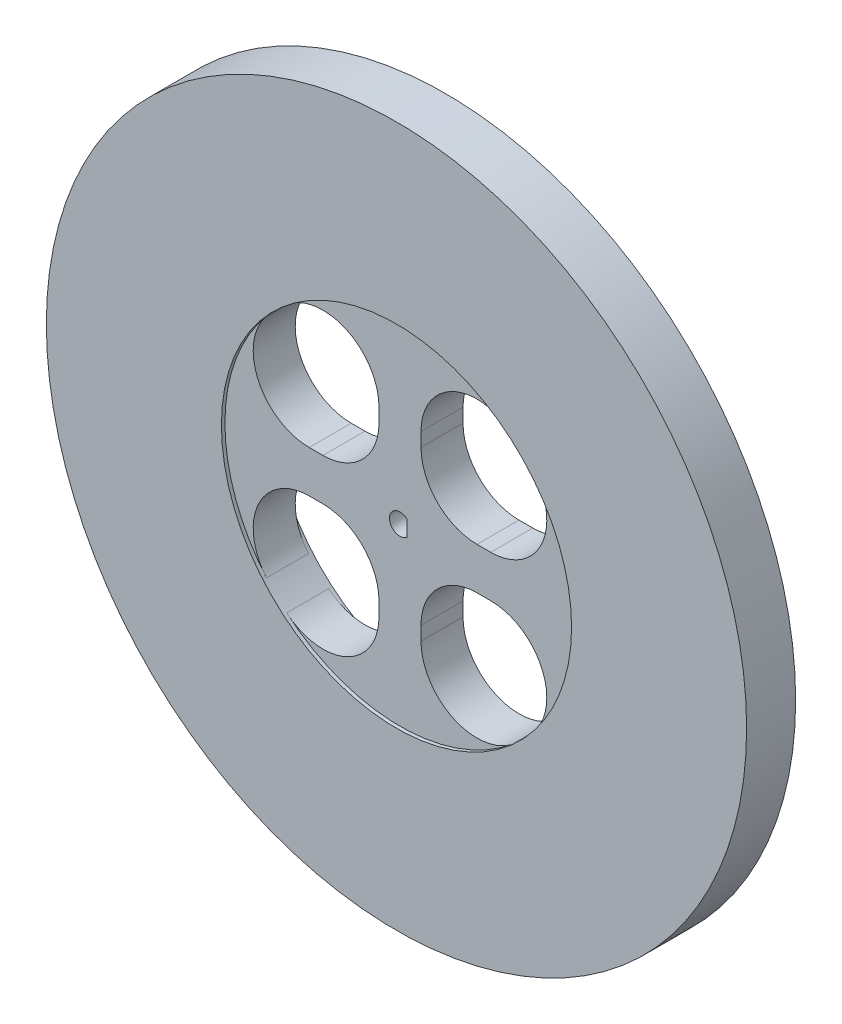
SolidWorks part; units mm, degrees
material "PET"
ref_plane "Front Plane" through (0, 0, 0) normal (0, 0, 1) x (1, 0, 0)
ref_plane "Top Plane" through (0, 0, 0) normal (0, 1, 0) x (1, 0, 0)
ref_plane "Right Plane" through (0, 0, 0) normal (1, 0, 0) x (0, 0, -1)
sketch "Sketch4" plane through (0, 0, 0) normal (0, 1, 0) x (1, 0, 0)
  line L0 (0, 11.6743) -> (0, -11.4125) construction
  line L2 (25, -3.5) -> (50, -3.5)
  line L3 (25, -3.5) -> (25, 3.5)
  line L4 (25, 3.5) -> (50, 3.5)
  line L5 (50, -3.5) -> (50, 3.5)
  line L6 (25, -3.5) -> (50, 3.5) construction
  line L7 (25, 3.5) -> (50, -3.5) construction
  point P3 (37.5, 0)
  dimension "D1" = 25
  dimension "D2" = 7
  dimension "D3" = 37.5
revolve "Revolve2" add sketch "Sketch4" angle 360 about L0
sketch "Sketch5" plane through (0, 0, 0) normal (0, 0, 1) x (1, 0, 0)
  line L0 (0, 25) -> (0, -25) construction
  line L1 (-3, 24.8193) -> (-3, 3)
  line L2 (-25, 0) -> (25, 0) construction
  line L3 (-24.8193, -3) -> (-3, -3)
  line L4 (3, 24.8193) -> (3, 3)
  line L5 (-24.8193, 3) -> (-3, 3)
  line L6 (3, 25) -> (3, -25) construction
  line L7 (-3, 25) -> (-3, -25) construction
  line L8 (-25, 3) -> (25, 3) construction
  line L9 (-25, -3) -> (25, -3) construction
  line L10 (3, 3) -> (24.8193, 3)
  line L11 (-3, -3) -> (-3, -24.8193)
  line L12 (3, -3) -> (24.8193, -3)
  line L13 (3, -3) -> (3, -24.8193)
  arc A0 (-24.8193, 3) -> (-24.8193, -3) centre (0, 0) ccw
  circle A1 centre (0, 0) radius 25 construction
  arc A2 (-3, 24.8193) -> (-24.8193, 3) centre (0, 0) ccw construction
  arc A3 (-24.8193, -3) -> (-3, -24.8193) centre (0, 0) ccw construction
  arc A4 (-3, -24.8193) -> (3, -24.8193) centre (0, 0) ccw
  arc A5 (3, -24.8193) -> (24.8193, -3) centre (0, 0) ccw construction
  arc A6 (24.8193, -3) -> (24.8193, 3) centre (0, 0) ccw
  arc A7 (24.8193, 3) -> (3, 24.8193) centre (0, 0) ccw construction
  arc A8 (3, 24.8193) -> (-3, 24.8193) centre (0, 0) ccw
  dimension "D1" = 3
  dimension "D2" = 3
extrude "Boss-Extrude3" add sketch "Sketch5" along normal blind 3 and the other way blind 3
fillet "Fillet2" radius 8 12 edges at (3, -3, 0) (-3, -3, 0) (-3, 3, 0) (3, 3, 0) (-3, 24.8193, 0) (3, 24.8193, 0) (24.8193, -3, 0) (24.8193, 3, 0) (-3, -24.8193, 0) (3, -24.8193, 0) (-24.8193, 3, 0) (-24.8193, -3, 0)
sketch "Sketch6" plane through (0, 0, 3) normal (0, 0, 1) x (1, 0, 0)
  line L0 (1, 1.118) -> (1, -1.118)
  arc A0 (1, 1.118) -> (1, -1.118) centre (0, 0) ccw
  arc A1 (1, -1.118) -> (1, 1.118) centre (0, 0) ccw construction
  dimension "D1" = 3
  dimension "D2" = 1
extrude "Cut-Extrude1" cut sketch "Sketch6" against normal up to next
